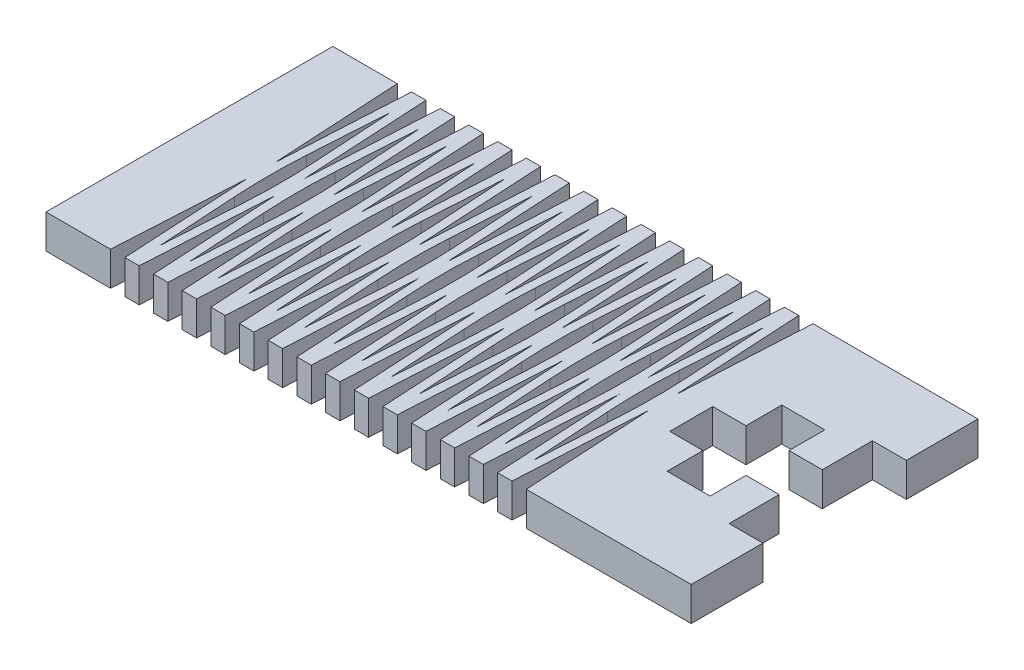
SolidWorks part; units mm, degrees
ref_plane "Front Plane" through (0, 0, 0) normal (0, 0, 1) x (1, 0, 0)
ref_plane "Top Plane" through (0, 0, 0) normal (0, 1, 0) x (1, 0, 0)
ref_plane "Right Plane" through (0, 0, 0) normal (1, 0, 0) x (0, 0, -1)
sketch "Sketch1" plane through (0, 0, 0) normal (0, 1, 0) x (1, 0, 0)
  line L0 (28.575, 6.35) -> (25.575, 6.35)
  line L1 (28.575, -12.7) -> (-28.575, -12.7)
  line L2 (28.575, -12.7) -> (28.575, -6.35)
  line L3 (28.575, 12.7) -> (-28.575, 12.7)
  line L4 (-28.575, -12.7) -> (-28.575, 12.7)
  line L5 (28.575, -12.7) -> (-28.575, 12.7) construction
  line L6 (28.575, 12.7) -> (-28.575, -12.7) construction
  line L7 (25.575, 6.35) -> (25.575, 1.905)
  line L8 (25.575, -6.35) -> (28.575, -6.35)
  line L9 (28.575, 6.35) -> (28.575, 12.7)
  line L10 (28.575, 6.35) -> (28.575, -6.35) construction
  line L11 (-28.575, 0) -> (28.575, 0) construction
  line L12 (15.875, 1.905) -> (18.82, 1.905)
  line L13 (15.875, 1.905) -> (15.875, -1.905)
  line L14 (15.875, -1.905) -> (18.82, -1.905)
  line L15 (18.82, 1.905) -> (18.82, 5.08)
  line L16 (15.875, 1.905) -> (25.575, -1.905) construction
  line L17 (15.875, -1.905) -> (25.575, 1.905) construction
  line L18 (25.575, -1.905) -> (25.575, -6.35)
  line L19 (22.63, -5.08) -> (18.82, -5.08)
  line L20 (22.63, -5.08) -> (22.63, -1.905)
  line L21 (22.63, 5.08) -> (18.82, 5.08)
  line L22 (18.82, -5.08) -> (18.82, -1.905)
  line L23 (22.63, 1.905) -> (25.575, 1.905)
  line L24 (22.63, 1.905) -> (22.63, 5.08)
  line L25 (22.63, -1.905) -> (25.575, -1.905)
  line L26 (18.82, 5.08) -> (22.63, -5.08) construction
  line L27 (22.63, 5.08) -> (18.82, -5.08) construction
  point P0 (0, 0)
  point P8 (20.725, 0)
  point P17 (15.875, 0)
  point P18 (20.725, 0)
  dimension "D1" = 57.15
  dimension "D2" = 25.4
  dimension "D3" = 12.7
  dimension "D4" = 3
  dimension "D5" = 3.81
  dimension "D6" = 6.35
  dimension "D7" = 12.7
  dimension "D9" = 3.81
  dimension "D10" = 10.16
extrude "Boss-Extrude1" add sketch "Sketch1" along normal blind 3
sketch "Sketch3" plane through (0, 3, 0) normal (0, 1, 0) x (1, 0, 0)
  line L0 (28.575, -12.7) -> (28.575, -6.35) construction
  line L1 (28.575, 12.7) -> (-28.575, 12.7) construction
  line L2 (-28.575, -12.7) -> (28.575, -12.7) construction
  line L4 (-28.575, 1.27) -> (25.575, 1.27) construction
  line L7 (-28.575, 12.7) -> (-28.575, -12.7) construction
  line L8 (25.575, 1.905) -> (25.575, 6.35) construction
  line L9 (25.575, -1.27) -> (-28.575, -1.27) construction
  line L10 (25.575, -6.35) -> (25.575, -1.905) construction
  line L11 (13.97, 12.7) -> (13.335, 1.27)
  line L12 (13.335, 1.27) -> (12.7, 12.7)
  line L13 (13.335, 12.7) -> (13.335, -12.7) construction
  line L14 (12.7, 12.7) -> (13.97, 12.7)
  line L15 (12.7, -12.7) -> (13.97, -12.7)
  line L16 (13.97, -12.7) -> (13.335, -1.27)
  line L17 (13.335, -1.27) -> (12.7, -12.7)
  dimension "D1" = 15.24
  dimension "D2" = 11.43
  dimension "D3" = 11.43
  dimension "D4" = 1.27
  dimension "D5" = 1.27
extrude "Cut-Extrude2" cut sketch "Sketch3" against normal through all
pattern_linear "LPattern1" count 15 spacing 2.54 along (-1, 0, 0) of "Cut-Extrude2"
sketch "Sketch4" plane through (0, 3, 0) normal (0, 1, 0) x (1, 0, 0)
  line L0 (12.065, 10.16) -> (12.5019, 3.1688)
  line L1 (12.5019, -3.1688) -> (12.065, -10.16)
  line L2 (12.065, -10.16) -> (11.6281, -3.1688)
  line L3 (11.6281, 3.1688) -> (12.065, 10.16)
  line L4 (12.065, 12.7) -> (12.065, -12.7) construction
  line L5 (12.7, 12.7) -> (11.43, 12.7) construction
  line L6 (11.43, -12.7) -> (12.7, -12.7) construction
  line L7 (0, 0) -> (15.875, 0) construction
  line L8 (15.875, -1.905) -> (15.875, 1.905) construction
  arc A0 (11.6281, -3.1688) -> (11.6281, 3.1688) centre (62.3291, 0) cw
  arc A1 (12.5019, -3.1688) -> (12.5019, 3.1688) centre (-38.1991, 0) ccw
  point P11 (0, 0)
  point P18 (11.43, 0)
  point P21 (12.7, 0)
  dimension "D4" = 50.8
  dimension "D5" = 50.8
  dimension "D1" = 2.54
  dimension "D2" = 2.54
  dimension "D3" = 1.27
extrude "Cut-Extrude3" cut sketch "Sketch4" against normal through all
pattern_linear "LPattern3" count 14 spacing 2.54 along (-1, 0, 0) of "Cut-Extrude3"
